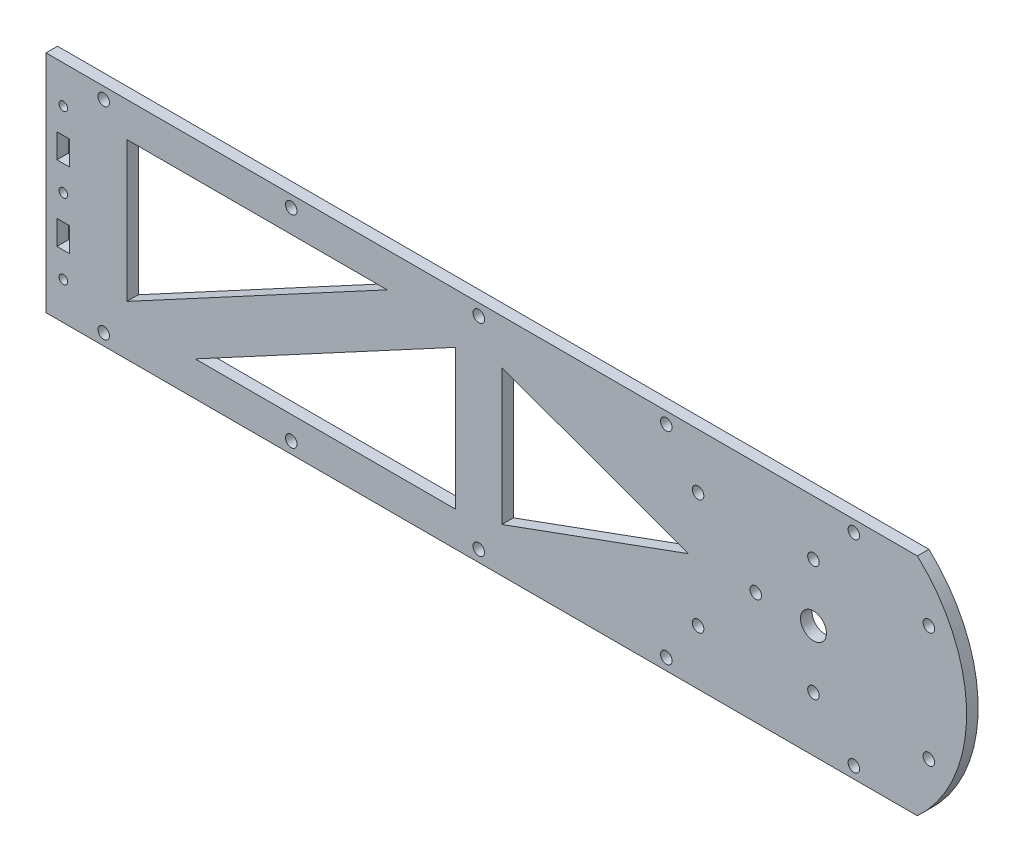
SolidWorks part; units mm, degrees
ref_plane "前视基准面" through (0, 0, 0) normal (0, 0, 1) x (1, 0, 0)
ref_plane "上视基准面" through (0, 0, 0) normal (0, 1, 0) x (1, 0, 0)
ref_plane "右视基准面" through (0, 0, 0) normal (1, 0, 0) x (0, 0, -1)
sketch "草图1" plane through (0, 0, 0) normal (0, 0, 1) x (1, 0, 0)
  line L0 (0, 0) -> (0, 13) construction
  line L1 (0, 13) -> (-8.8556, 13) construction
  line L2 (-2.2, 17.2) -> (2.2, 17.2)
  line L3 (-2.2, 17.2) -> (-2.2, 8.8)
  line L4 (-2.2, 8.8) -> (2.2, 8.8)
  line L5 (2.2, 17.2) -> (2.2, 8.8)
  line L6 (-2.2, 17.2) -> (2.2, 8.8) construction
  line L7 (-2.2, 8.8) -> (2.2, 17.2) construction
  line L8 (0, 26) -> (7.7263, 26) construction
  line L13 (0, 0) -> (-13.815, 0) construction
  line L14 (-2.2, -8.8) -> (2.2, -17.2) construction
  line L15 (-2.2, -17.2) -> (2.2, -8.8) construction
  line L16 (0, -13) -> (-8.8556, -13) construction
  line L17 (2.2, -17.2) -> (2.2, -8.8)
  line L18 (-2.2, -8.8) -> (2.2, -8.8)
  line L19 (-2.2, -17.2) -> (-2.2, -8.8)
  line L20 (-2.2, -17.2) -> (2.2, -17.2)
  line L21 (0, 0) -> (260, 0) construction
  line L22 (-6, 39) -> (246, 39) construction
  line L23 (-6, 39) -> (-6, -39)
  line L24 (-6, -39) -> (246, -39) construction
  line L25 (246, 39) -> (246, -39) construction
  line L26 (260, 20) -> (300, 20) construction
  line L27 (300, 20) -> (300, -20) construction
  line L28 (-6, -39) -> (296.0243, -39)
  line L29 (-6, 39) -> (296.0243, 39)
  line L30 (294, -39) -> (294, -35) construction
  line L31 (274, -35) -> (274, -39) construction
  line L32 (274, -35) -> (294, -35) construction
  line L33 (14, -35) -> (144, -35) construction
  line L34 (144, -35) -> (144, 35) construction
  line L35 (144, 35) -> (14, 35) construction
  line L36 (14, 35) -> (14, -35) construction
  line L37 (14, -35) -> (144, 35) construction
  line L38 (22, -21.6063) -> (112.2688, 27)
  line L39 (112.2688, 27) -> (22, 27)
  line L40 (22, 27) -> (22, -21.6063)
  line L41 (45.7312, -27) -> (136, -27)
  line L42 (136, -27) -> (136, 21.6063)
  line L43 (45.7312, -27) -> (136, 21.6063)
  line L44 (144, -35) -> (240, 0) construction
  line L45 (240, 0) -> (144, 35) construction
  line L46 (152, -23.5682) -> (216.6443, 0)
  line L47 (216.6443, 0) -> (152, 23.5682)
  line L48 (152, -23.5682) -> (152, 23.5682)
  circle A0 centre (0, 0) radius 1.5
  circle A1 centre (0, 26) radius 1.5
  circle A2 centre (0, -26) radius 1.5
  circle A3 centre (260, 0) radius 4.5
  circle A4 centre (260, 20) radius 2
  circle A5 centre (240, 0) radius 2
  circle A9 centre (300, 20) radius 2
  circle A10 centre (300, -20) radius 2
  arc A12 (296.0243, -39) -> (296.0243, 39) centre (260, 0) ccw
  circle A13 centre (220, 20) radius 2
  circle A14 centre (220, -20) radius 2
  circle A15 centre (260, -20) radius 2
  circle A16 centre (274, -35) radius 2
  circle A17 centre (209, -35) radius 2
  circle A18 centre (144, -35) radius 2
  circle A19 centre (79, -35) radius 2
  circle A20 centre (14, -35) radius 2
  circle A21 centre (209, 35) radius 2
  circle A22 centre (144, 35) radius 2
  circle A23 centre (79, 35) radius 2
  circle A24 centre (14, 35) radius 2
  circle A25 centre (274, 35) radius 2
  point P25 (-6, 0)
  dimension "D1" = 3
  dimension "D8" = 9
  dimension "D10" = 20
  dimension "D13" = 40
  dimension "D11" = 40
  dimension "D14" = 300
  dimension "D15" = 20
  dimension "D18" = 8
  dimension "D2" = 13
  dimension "D3" = 4.4
  dimension "D4" = 8.4
  dimension "D5" = 78
  dimension "D6" = 252
  dimension "D7" = 6
  dimension "D9" = 260
  dimension "D12" = 20
  dimension "D19" = 8
  dimension "D20" = 8
  dimension "D16" = 5
  dimension "D17" = 2
extrude "凸台-拉伸1" add sketch "草图1" along normal blind 4
